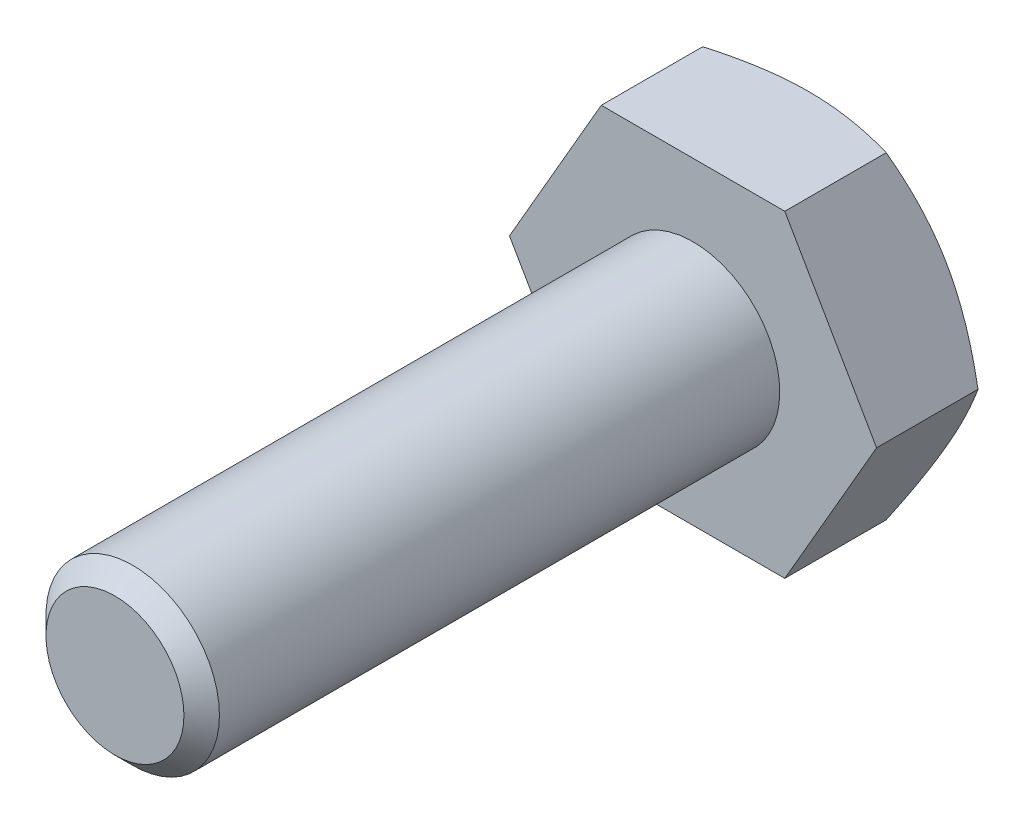
SolidWorks part; units mm, degrees
material "Plain Carbon Steel"
ref_plane "Front Plane" through (0, 0, 0) normal (0, 0, 1) x (1, 0, 0)
ref_plane "Top Plane" through (0, 0, 0) normal (0, 1, 0) x (1, 0, 0)
ref_plane "Right Plane" through (0, 0, 0) normal (1, 0, 0) x (0, 0, -1)
sketch "Sketch1" plane through (0, 0, 0) normal (0, 0, 1) x (1, 0, 0)
  line L1 (3.1754, 0) -> (1.5877, 2.75)
  line L2 (1.5877, 2.75) -> (-1.5877, 2.75)
  line L3 (-1.5877, 2.75) -> (-3.1754, 0)
  line L4 (-3.1754, 0) -> (-1.5877, -2.75)
  line L5 (-1.5877, -2.75) -> (1.5877, -2.75)
  line L6 (1.5877, -2.75) -> (3.1754, 0)
  circle A0 centre (0, 0) radius 2.75 construction
  dimension "D1" = 5.5
extrude "Extrude1" add sketch "Sketch1" along normal blind 2
sketch "Sketch2" plane through (0, 0, 2) normal (0, 0, 1) x (1, 0, 0)
  circle A0 centre (0, 0) radius 1.5
  dimension "D1" = 3
extrude "Extrude2" add sketch "Sketch2" along normal blind 10
cosmetic thread "Cosmetic Thread1" parameters "D2"=2.386
sketch "Sketch3" plane through (0, 0, 0) normal (1, 0, 0) x (0, 0, -1)
  line L0 (0, 2.75) -> (0, 102.75)
  line L1 (0, 102.75) -> (-57.735, 102.75)
  line L2 (-57.735, 102.75) -> (0, 2.75)
  line L3 (0, 0) -> (11.4679, 0) construction
  dimension "D1" = 30
  dimension "D2" = 100
revolve "Cut-Revolve1" cut sketch "Sketch3" angle 360 about L3
chamfer "Chamfer1" distance 0.307 angle 45 1 edges at (1.5, 0, 12)
